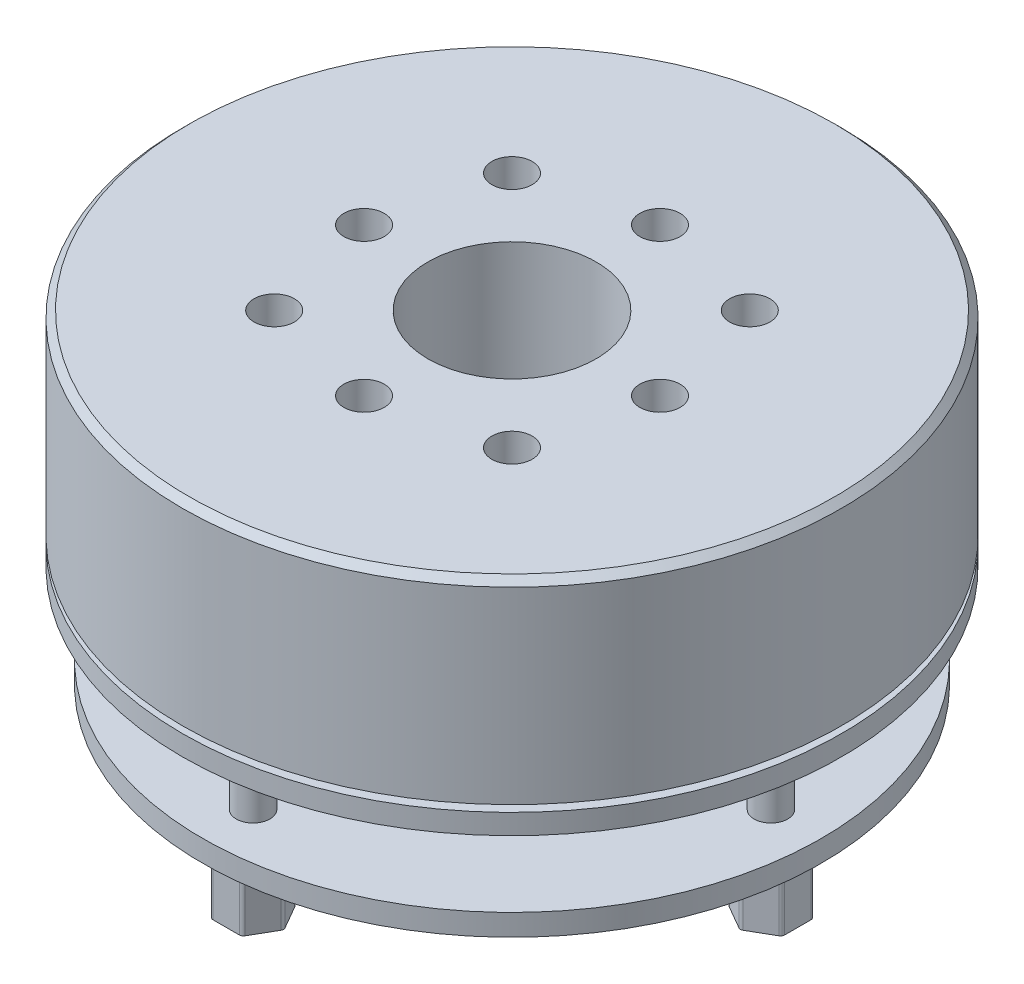
SolidWorks part; units mm, degrees
ref_plane "前视基准面" through (0, 0, 0) normal (0, 0, 1) x (1, 0, 0)
ref_plane "上视基准面" through (0, 0, 0) normal (0, 1, 0) x (1, 0, 0)
ref_plane "右视基准面" through (0, 0, 0) normal (1, 0, 0) x (0, 0, -1)
sketch "草图1" plane through (0, 0, 0) normal (0, 0, 1) x (1, 0, 0)
  line L1 (24, 22.1) -> (0, 22.1)
  line L4 (24.5, 21.6) -> (24.5, 7.6)
  line L6 (24.5, 7.6) -> (23.5, 7.6)
  line L7 (23.5, 7.6) -> (23.5, 7.1)
  line L8 (23.5, 7.1) -> (24.5, 7.1)
  line L9 (24.5, 7.1) -> (24.5, 5.6)
  line L10 (24.5, 21.6) -> (24, 22.1)
  line L12 (24.5, 5.6) -> (22, 5.6)
  line L13 (22, 5.6) -> (22, 4.1)
  line L14 (22, 4.1) -> (8.3, 4.1)
  line L17 (0, 4.5453) -> (0, 22.1)
  line L22 (0, 4.5453) -> (0, 3.1)
  line L23 (0, 3.1) -> (8.3, 3.1)
  line L24 (8.3, 3.1) -> (8.3, 4.1)
  dimension "D2" = 18
  dimension "D3" = 135
  dimension "D4" = 14
  dimension "D5" = 1
  dimension "D6" = 0.5
  dimension "D7" = 1.5
  dimension "D8" = 1.5
  dimension "D9" = 2.5
  dimension "D10" = 8.3
  dimension "D11" = 1
  dimension "D12" = 3.1
  dimension "D13" = 1.4453
  dimension "D14" = 24.5
revolve "旋转1" add sketch "草图1" angle 360 about L17
sketch "草图2" plane through (0, 22.1, 0) normal (0, 1, 0) x (1, 0, 0)
  line L0 (0, 0) -> (0, 25.9186) construction
  line L2 (-8.8388, -8.8388) -> (8.8388, -8.8388) construction
  line L3 (-8.8388, -8.8388) -> (-8.8388, 8.8388) construction
  line L4 (-8.8388, 8.8388) -> (8.8388, 8.8388) construction
  line L5 (8.8388, -8.8388) -> (8.8388, 8.8388) construction
  line L6 (0, 8.8388) -> (0, -8.8388) construction
  line L7 (-8.8388, 0) -> (8.8388, 0) construction
  circle A0 centre (0, 0) radius 11 construction
  circle A1 centre (0, 11) radius 1.5
  circle A2 centre (11, 0) radius 1.5
  circle A3 centre (0, -11) radius 1.5
  circle A4 centre (-11, 0) radius 1.5
  circle A5 centre (0, 0) radius 12.5 construction
  circle A8 centre (8.8388, 8.8388) radius 1.5
  circle A10 centre (8.8388, -8.8388) radius 1.5
  circle A12 centre (-8.8388, -8.8388) radius 1.5
  circle A14 centre (-8.8388, 8.8388) radius 1.5
  point P15 (0, 0)
  point P33 (0, 0)
  dimension "D1" = 4
  dimension "D2" = 22
  dimension "D3" = 25
  dimension "D4" = 3
extrude "切除-拉伸1" cut sketch "草图2" against normal blind 3
sketch "草图3" plane through (0, 22.1, 0) normal (0, 1, 0) x (1, 0, 0)
  circle A0 centre (0, 0) radius 6.25
  dimension "D1" = 12.5
extrude "切除-拉伸2" cut sketch "草图3" against normal blind 18
sketch "草图5" [suppressed] plane through (0, 4.1, 0) normal (0, -1, 0) x (1, 0, 0)
  line L0 (0, 0) -> (0, 24.6178) construction
  circle A0 centre (0, 0) radius 12.5 construction
  circle A2 centre (0, 12.5) radius 1
  circle A4 centre (12.5, 0) radius 1
  circle A5 centre (0, -12.5) radius 1
  circle A6 centre (-12.5, 0) radius 1
  point P17 (0, 0)
  dimension "D1" = 4
sketch "草图6" plane through (0, 4.1, 0) normal (0, -1, 0) x (1, 0, 0)
  circle A0 centre (0, 0) radius 19.25 construction
  circle A1 centre (0, 19.25) radius 1.25
  circle A2 centre (19.25, 0) radius 1.25
  circle A3 centre (0, -19.25) radius 1.25
  circle A4 centre (-19.25, 0) radius 1.25
  point P14 (0, 0)
  dimension "D1" = 4
  dimension "D2" = 38.5
  dimension "D3" = 2.5
extrude "凸台-拉伸1" add sketch "草图6" along normal blind 4.5
sketch "草图7" plane through (0, -0.4, 0) normal (0, -1, 0) x (1, 0, 0)
  circle A0 centre (0, 0) radius 23
  dimension "D1" = 46
extrude "凸台-拉伸2" add sketch "草图7" along normal blind 1.6
sketch "草图10" plane through (0, -2, 0) normal (0, -1, 0) x (1, 0, 0)
  line L0 (21.1, 1.2413) -> (19.4, 2.2228)
  line L1 (-1.2413, 21.1) -> (-2.2228, 19.4)
  line L2 (-2.2228, 19.1) -> (-1.2413, 17.4)
  line L3 (-0.9815, 17.25) -> (0.9815, 17.25)
  line L4 (1.2413, 17.4) -> (2.2228, 19.1)
  line L5 (2.2228, 19.4) -> (1.2413, 21.1)
  line L6 (0.9815, 21.25) -> (-0.9815, 21.25)
  line L7 (19.1, 2.2228) -> (17.4, 1.2413)
  line L8 (17.25, 0.9815) -> (17.25, -0.9815)
  line L9 (17.4, -1.2413) -> (19.1, -2.2228)
  line L10 (19.4, -2.2228) -> (21.1, -1.2413)
  line L11 (21.25, -0.9815) -> (21.25, 0.9815)
  line L12 (1.2413, -21.1) -> (2.2228, -19.4)
  line L13 (2.2228, -19.1) -> (1.2413, -17.4)
  line L14 (0.9815, -17.25) -> (-0.9815, -17.25)
  line L15 (-1.2413, -17.4) -> (-2.2228, -19.1)
  line L16 (-2.2228, -19.4) -> (-1.2413, -21.1)
  line L17 (-0.9815, -21.25) -> (0.9815, -21.25)
  line L18 (-21.1, -1.2413) -> (-19.4, -2.2228)
  line L19 (-19.1, -2.2228) -> (-17.4, -1.2413)
  line L20 (-17.25, -0.9815) -> (-17.25, 0.9815)
  line L21 (-17.4, 1.2413) -> (-19.1, 2.2228)
  line L22 (-19.4, 2.2228) -> (-21.1, 1.2413)
  line L23 (-21.25, 0.9815) -> (-21.25, -0.9815)
  circle A0 centre (0, 0) radius 19.25 construction
  circle A1 centre (0, 19.25) radius 1.25
  circle A2 centre (19.25, 0) radius 1.25
  circle A3 centre (0, -19.25) radius 1.25
  circle A4 centre (-19.25, 0) radius 1.25
  circle A5 centre (0, 19.25) radius 2 construction
  arc A6 (1.2413, 21.1) -> (0.9815, 21.25) centre (0.9815, 20.95) ccw
  arc A7 (2.2228, 19.1) -> (2.2228, 19.4) centre (1.963, 19.25) ccw
  arc A8 (0.9815, 17.25) -> (1.2413, 17.4) centre (0.9815, 17.55) ccw
  arc A9 (-1.2413, 17.4) -> (-0.9815, 17.25) centre (-0.9815, 17.55) ccw
  arc A10 (-2.2228, 19.4) -> (-2.2228, 19.1) centre (-1.963, 19.25) ccw
  arc A11 (-1.2413, 21.1) -> (-0.9815, 21.25) centre (-0.9815, 20.95) cw
  arc A12 (21.1, 1.2413) -> (21.25, 0.9815) centre (20.95, 0.9815) cw
  arc A13 (19.4, 2.2228) -> (19.1, 2.2228) centre (19.25, 1.963) ccw
  arc A14 (17.4, 1.2413) -> (17.25, 0.9815) centre (17.55, 0.9815) ccw
  arc A15 (17.25, -0.9815) -> (17.4, -1.2413) centre (17.55, -0.9815) ccw
  arc A16 (19.1, -2.2228) -> (19.4, -2.2228) centre (19.25, -1.963) ccw
  arc A17 (21.1, -1.2413) -> (21.25, -0.9815) centre (20.95, -0.9815) ccw
  arc A18 (1.2413, -21.1) -> (0.9815, -21.25) centre (0.9815, -20.95) cw
  arc A19 (2.2228, -19.4) -> (2.2228, -19.1) centre (1.963, -19.25) ccw
  arc A20 (1.2413, -17.4) -> (0.9815, -17.25) centre (0.9815, -17.55) ccw
  arc A21 (-0.9815, -17.25) -> (-1.2413, -17.4) centre (-0.9815, -17.55) ccw
  arc A22 (-2.2228, -19.1) -> (-2.2228, -19.4) centre (-1.963, -19.25) ccw
  arc A23 (-1.2413, -21.1) -> (-0.9815, -21.25) centre (-0.9815, -20.95) ccw
  arc A24 (-21.1, -1.2413) -> (-21.25, -0.9815) centre (-20.95, -0.9815) cw
  arc A25 (-19.4, -2.2228) -> (-19.1, -2.2228) centre (-19.25, -1.963) ccw
  arc A26 (-17.4, -1.2413) -> (-17.25, -0.9815) centre (-17.55, -0.9815) ccw
  arc A27 (-17.25, 0.9815) -> (-17.4, 1.2413) centre (-17.55, 0.9815) ccw
  arc A28 (-19.1, 2.2228) -> (-19.4, 2.2228) centre (-19.25, 1.963) ccw
  arc A29 (-21.1, 1.2413) -> (-21.25, 0.9815) centre (-20.95, 0.9815) ccw
  point P14 (0, 0)
  point P24 (2.3094, 19.25)
  point P31 (-2.3094, 19.25)
  point P90 (0, 0)
  dimension "D1" = 4
  dimension "D2" = 38.5
  dimension "D3" = 2.5
  dimension "D5" = 0.3
  dimension "D4" = 4
  dimension "D6" = 4
extrude "凸台-拉伸3" add sketch "草图10" along normal blind 5 separate body
